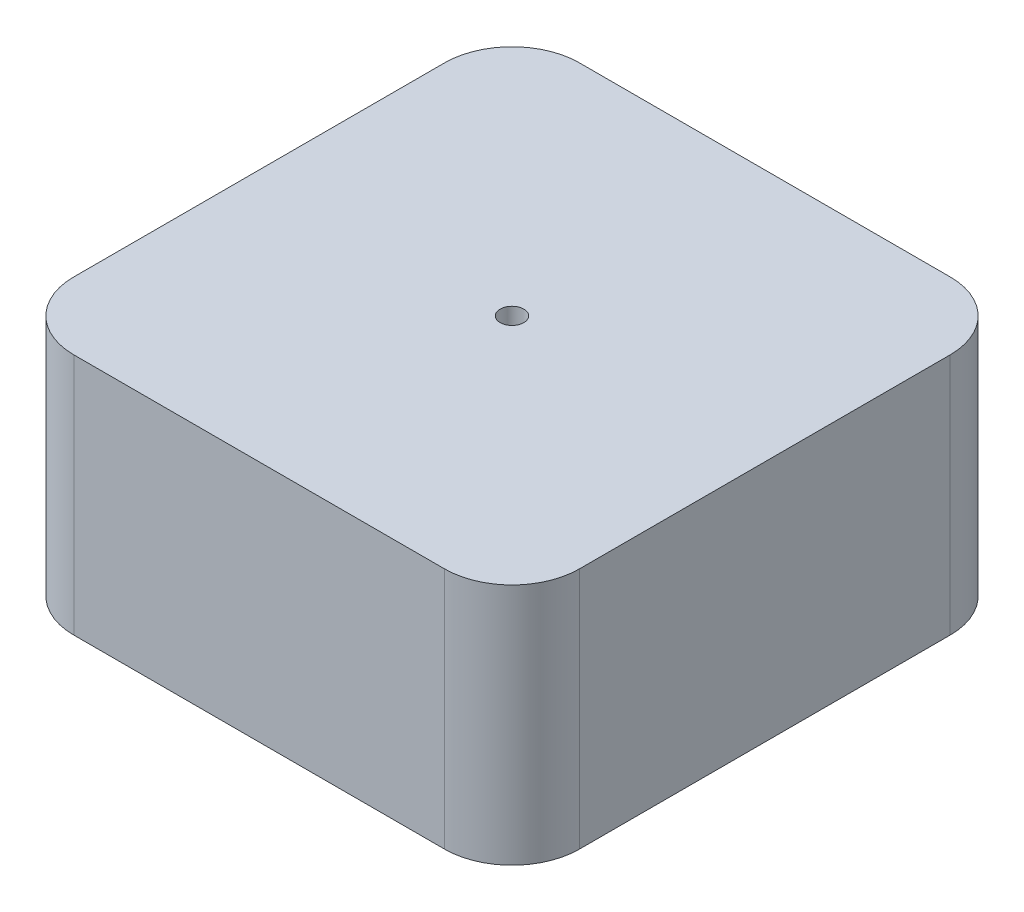
SolidWorks part; units mm, degrees
ref_plane "Front Plane" through (0, 0, 0) normal (0, 0, 1) x (1, 0, 0)
ref_plane "Top Plane" through (0, 0, 0) normal (0, 1, 0) x (1, 0, 0)
ref_plane "Right Plane" through (0, 0, 0) normal (1, 0, 0) x (0, 0, -1)
sketch "Base Top Face Profile" plane through (0, 0, 0) normal (0, 1, 0) x (1, 0, 0)
  line L0 (-55, -75) -> (55, -75)
  line L1 (-75, -55) -> (-75, 55)
  line L2 (-55, 75) -> (55, 75)
  line L3 (75, -55) -> (75, 55)
  line L4 (-75, -75) -> (75, 75) construction
  line L5 (-75, 75) -> (75, -75) construction
  arc A0 (-75, -55) -> (-55, -75) centre (-55, -55) ccw
  arc A1 (55, -75) -> (75, -55) centre (55, -55) ccw
  arc A2 (75, 55) -> (55, 75) centre (55, 55) ccw
  arc A3 (-75, 55) -> (-55, 75) centre (-55, 55) cw
  point P0 (0, 0)
extrude "Base Walls" add sketch "Base Top Face Profile" against normal blind 72
shell "Box Shell" thickness 5
sketch "Side Wall Features" plane through (-70, 0, 0) normal (1, 0, 0) x (0, 0, -1)
  line L0 (55, -5) -> (-55, -5)
  line L1 (55, -5) -> (-55, -5) construction
  line L2 (0, -3.1928) -> (0, -86.6846) construction
sketch "Shaft Hole Profile" plane through (0, 0, 0) normal (0, 1, 0) x (1, 0, 0)
  circle A0 centre (0, 0) radius 3.5
  dimension "D1" = 7
extrude "Cut-Extrude1" cut sketch "Shaft Hole Profile" against normal through all contours A0
ref_plane "Plane1" through (0, -5, 0) normal (0, 1, 0) x (1, 0, 0)
